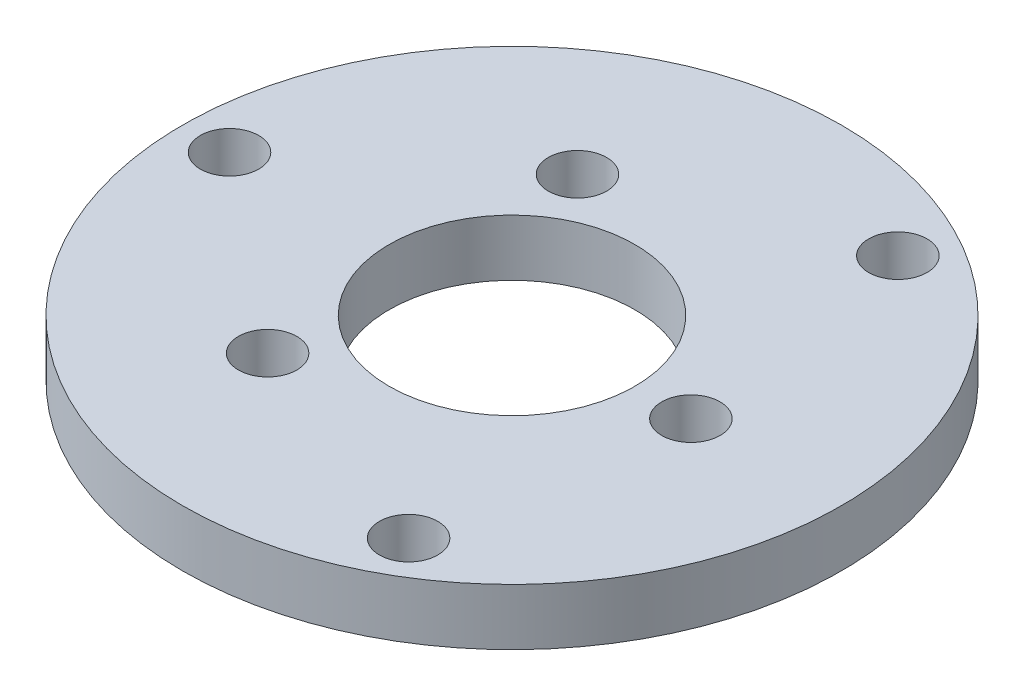
SolidWorks part; units mm, degrees
ref_plane "前视基准面" through (0, 0, 0) normal (0, 0, 1) x (1, 0, 0)
ref_plane "上视基准面" through (0, 0, 0) normal (0, 1, 0) x (1, 0, 0)
ref_plane "右视基准面" through (0, 0, 0) normal (1, 0, 0) x (0, 0, -1)
other "Configuration Table"
sketch "草图1" plane through (0, 0, 0) normal (0, 1, 0) x (1, 0, 0)
  circle A0 centre (0, 0) radius 17.5
  circle A1 centre (0, 0) radius 15 construction
  circle A2 centre (0, 0) radius 12.5 construction
  circle A3 centre (0, 0) radius 6.525
  circle A4 centre (-15, 0) radius 2.5 construction
  circle A5 centre (-15, 0) radius 1.55
  circle A6 centre (7.5, 12.9904) radius 1.55
  circle A7 centre (7.5, -12.9904) radius 1.55
  circle A8 centre (0, 0) radius 9.5 construction
  circle A9 centre (9.5, 0) radius 1.55
  circle A10 centre (-4.75, -8.2272) radius 1.55
  circle A11 centre (-4.75, 8.2272) radius 1.55
  point P15 (0, 0)
  point P23 (0, 0)
  dimension "D1" = 25
  dimension "D2" = 5
  dimension "D3" = 3.1
  dimension "D5" = 19
  dimension "D6" = 13.05
  dimension "D7" = 3.1
  dimension "D4" = 3
  dimension "D8" = 3
extrude "凸台-拉伸1" add sketch "草图1" along normal blind 3
